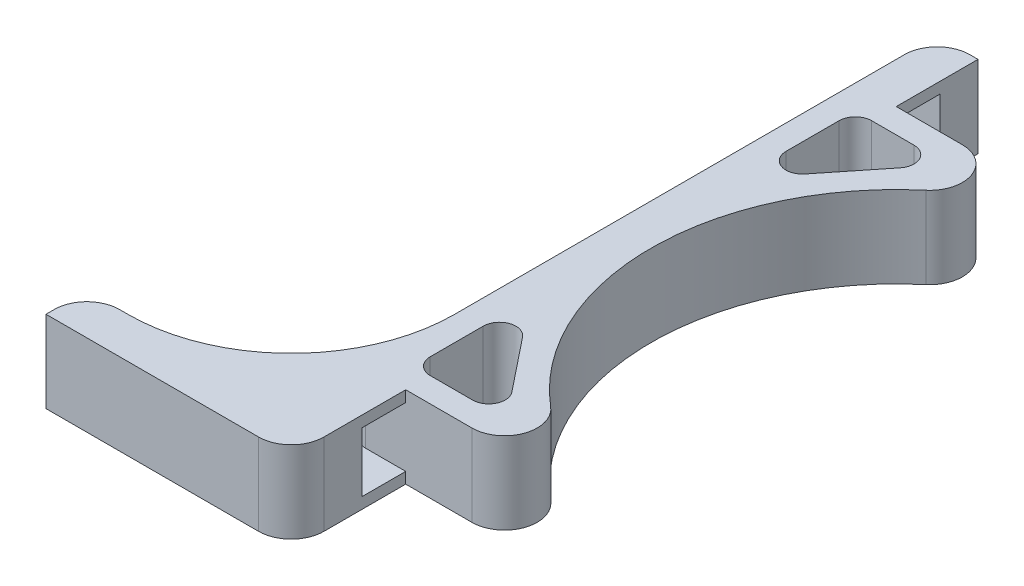
SolidWorks part; units mm, degrees
ref_plane "Front Plane" through (0, 0, 0) normal (0, 0, 1) x (1, 0, 0)
ref_plane "Top Plane" through (0, 0, 0) normal (0, 1, 0) x (1, 0, 0)
ref_plane "Right Plane" through (0, 0, 0) normal (1, 0, 0) x (0, 0, -1)
sketch "Sketch1" plane through (0, 0, 0) normal (0, 1, 0) x (1, 0, 0)
  line L0 (0, 0) -> (16.51, 0)
  line L1 (19.05, 2.54) -> (19.05, 53.34) construction
  line L2 (19.05, 53.34) -> (18.415, 53.34)
  line L3 (15.875, 50.8) -> (15.875, 15.875)
  line L4 (3.175, 3.175) -> (2.54, 3.175)
  line L5 (0, 0.635) -> (0, 0)
  line L6 (38.1, 46.99) -> (19.05, 46.99)
  line L7 (19.05, 46.99) -> (19.05, 53.34)
  line L8 (19.05, 2.54) -> (19.05, 8.89)
  line L9 (19.05, 8.89) -> (38.1, 8.89)
  line L10 (15.875, 8.89) -> (28.9321, 8.89) construction
  line L11 (28.9321, 8.89) -> (15.875, 25.2457) construction
  line L12 (15.875, 25.2457) -> (15.875, 8.89) construction
  line L13 (38.1, 27.94) -> (50038.1, 27.94) construction
  line L17 (24.9737, 10.795) -> (17.78, 19.806)
  line L18 (17.78, 19.806) -> (17.78, 10.795)
  line L19 (17.78, 10.795) -> (24.9737, 10.795)
  line L20 (17.78, 45.085) -> (24.9737, 45.085)
  line L21 (17.78, 36.074) -> (17.78, 45.085)
  line L22 (24.9737, 45.085) -> (17.78, 36.074)
  arc A0 (15.875, 15.875) -> (3.175, 3.175) centre (3.175, 15.875) cw
  arc A1 (19.05, 2.54) -> (16.51, 0) centre (16.51, 2.54) cw
  circle A2 centre (38.1, 27.94) radius 19.05 construction
  arc A3 (38.1, 46.99) -> (38.1, 8.89) centre (38.1, 27.94) ccw
  arc A4 (2.54, 3.175) -> (0, 0.635) centre (2.54, 0.635) ccw
  arc A5 (18.415, 53.34) -> (15.875, 50.8) centre (18.415, 50.8) ccw
  circle A6 centre (15.0112, 4.0388) radius 4.0388 construction
  point P15 (19.05, 27.94)
  point P36 (0, 3.175)
  point P39 (15.875, 53.34)
  dimension "D1" = 12.7
  dimension "D4" = 2.54
  dimension "D7" = 38.1
  dimension "D9" = 2.54
  dimension "D2" = 3.175
  dimension "D3" = 3.175
  dimension "D5" = 19.05
  dimension "D6" = 50.8
  dimension "D8" = 1.905
extrude "Boss-Extrude1" add sketch "Sketch1" along normal blind 6.35
fillet "Fillet1" radius 2.54 2 edges at (38.1, 3.175, -8.89) (38.1, 3.175, -46.99)
sketch "Sketch2" plane through (19.05, 0, 0) normal (1, 0, 0) x (0, 0, -1)
  line L0 (0, 3.175) -> (-50000, 3.175) construction
  line L1 (0, 6.35) -> (0, 0) construction
  line L2 (8.89, 6.35) -> (8.89, 0) construction
  line L3 (8.89, 5.4902) -> (5.498, 5.4902)
  line L4 (8.89, 5.4902) -> (8.89, 0.8598)
  line L5 (8.89, 0.8598) -> (5.498, 0.8598)
  line L6 (5.498, 5.4902) -> (5.498, 0.8598)
  line L7 (46.99, 6.35) -> (46.99, 0) construction
  line L8 (46.99, 5.4902) -> (50.382, 5.4902)
  line L9 (46.99, 5.4902) -> (46.99, 0.8598)
  line L10 (46.99, 0.8598) -> (50.382, 0.8598)
  line L11 (50.382, 5.4902) -> (50.382, 0.8598)
  point P4 (0, 3.175)
  point P17 (5.498, 3.175)
  point P18 (50.382, 3.175)
extrude "Cut-Extrude1" cut sketch "Sketch2" against normal through all
fillet "Fillet2" radius 1.27 8 edges at (17.78, 3.175, -19.806) (24.9737, 3.175, -10.795) (17.78, 3.175, -10.795) (17.78, 3.175, -36.074) (17.78, 3.175, -45.085) (24.9737, 3.175, -45.085) (13.7816, 3.175, -8.89) (15.875, 3.175, -46.99)
